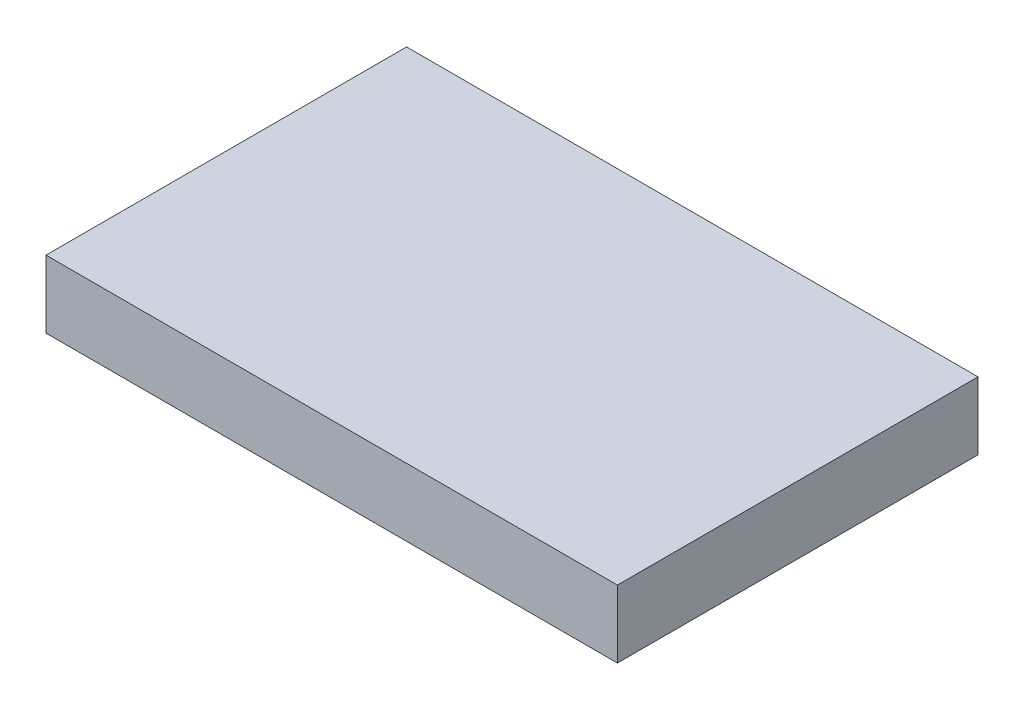
SolidWorks part; units mm, degrees
ref_plane "Front Plane" through (0, 0, 0) normal (0, 0, 1) x (1, 0, 0)
ref_plane "Top Plane" through (0, 0, 0) normal (0, 1, 0) x (1, 0, 0)
ref_plane "Right Plane" through (0, 0, 0) normal (1, 0, 0) x (0, 0, -1)
sketch "Sketch2" plane through (0, 0, 0) normal (0, 1, 0) x (1, 0, 0)
  line L0 (53.7067, -24.6521) -> (53.7067, 87.8022) construction
  line L1 (0, 0) -> (107.4134, 0)
  line L2 (0, 0) -> (0, 67.7799)
  line L3 (0, 67.7799) -> (107.4134, 67.7799)
  line L4 (107.4134, 0) -> (107.4134, 67.7799)
extrude "Extrude2" add sketch "Sketch2" against normal blind 12.7
